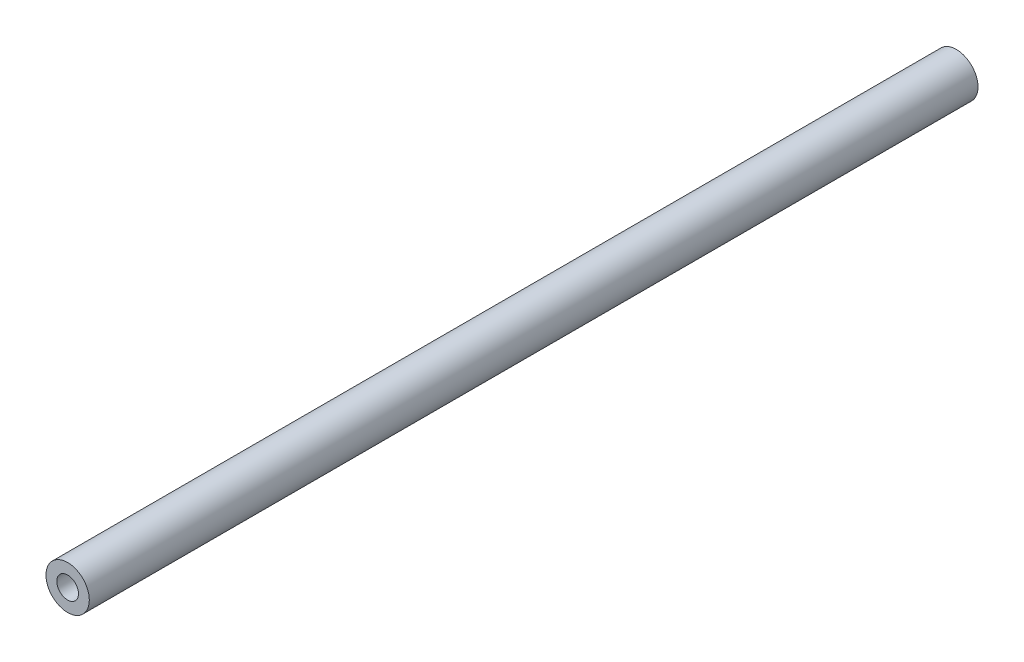
SolidWorks part; units mm, degrees
ref_plane "Přední rovina" through (0, 0, 0) normal (0, 0, 1) x (1, 0, 0)
ref_plane "Horní rovina" through (0, 0, 0) normal (0, 1, 0) x (1, 0, 0)
ref_plane "Pravá rovina" through (0, 0, 0) normal (1, 0, 0) x (0, 0, -1)
sketch "Skica1" plane through (0, 0, 0) normal (0, 0, 1) x (1, 0, 0)
  circle A0 centre (0, 0) radius 2
  circle A1 centre (0, 0) radius 1
extrude "Přidat vysunutím1" add sketch "Skica1" along normal blind 82
